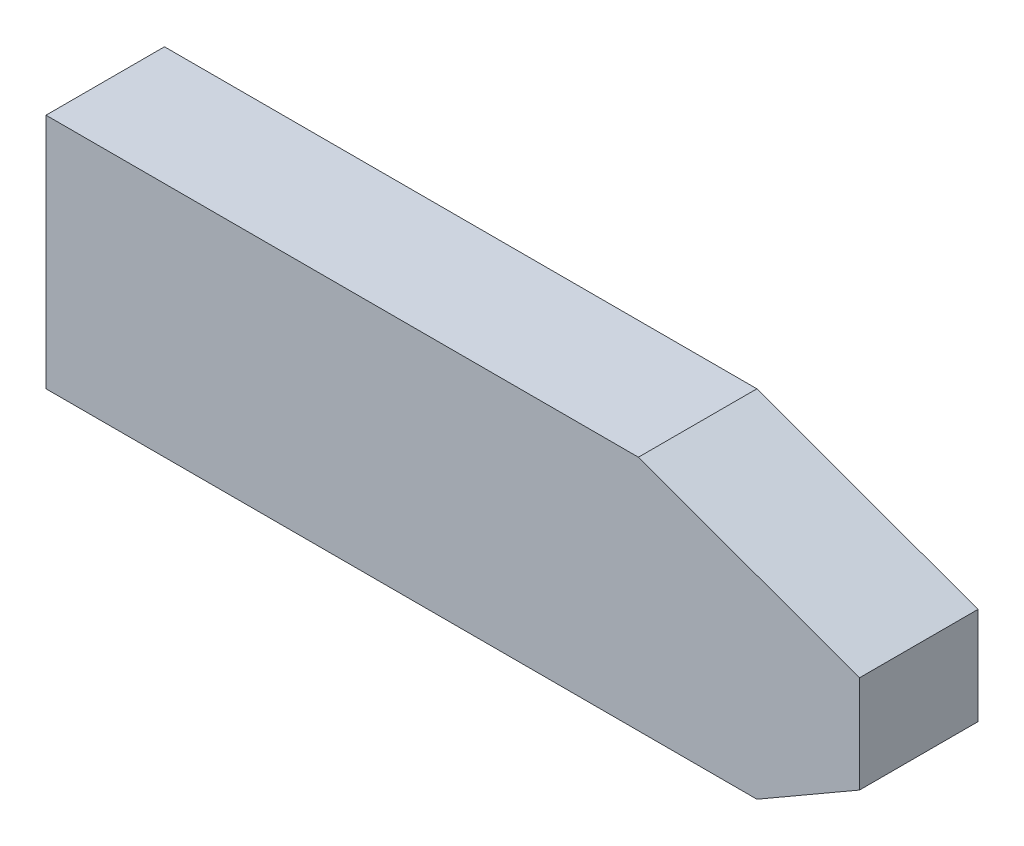
SolidWorks part; units mm, degrees
material "6061 Alloy"
ref_plane "Front Plane" through (0, 0, 0) normal (0, 0, 1) x (1, 0, 0)
ref_plane "Top Plane" through (0, 0, 0) normal (0, 1, 0) x (1, 0, 0)
ref_plane "Right Plane" through (0, 0, 0) normal (1, 0, 0) x (0, 0, -1)
sketch "Sketch2" plane through (0, 0, 0) normal (0, 0, 1) x (1, 0, 0)
  line L0 (0, 0) -> (152.4, 0)
  line L1 (152.4, 0) -> (174.397, 12.7)
  line L2 (174.397, 12.7) -> (174.397, 33.5489)
  line L3 (174.397, 33.5489) -> (127, 50.8)
  line L4 (127, 50.8) -> (0, 50.8)
  line L5 (0, 50.8) -> (0, 0)
  point P7 (6.1788, 1.322)
  point P8 (6.866, 0.5)
  point P9 (7.121, 1.228)
  point P10 (6.866, 1.3199)
  point P11 (6.9191, 1.3015)
  point P12 (6.866, 1.3201)
  dimension "D1" = 152.4
  dimension "D2" = 50.8
  dimension "D3" = 127
  dimension "D4" = 30
  dimension "D5" = 25.4
  dimension "D6" = 20
extrude "Boss-Extrude1" add sketch "Sketch2" along normal blind 25.4 contours L4 L5 L0 L1 L2 L3
